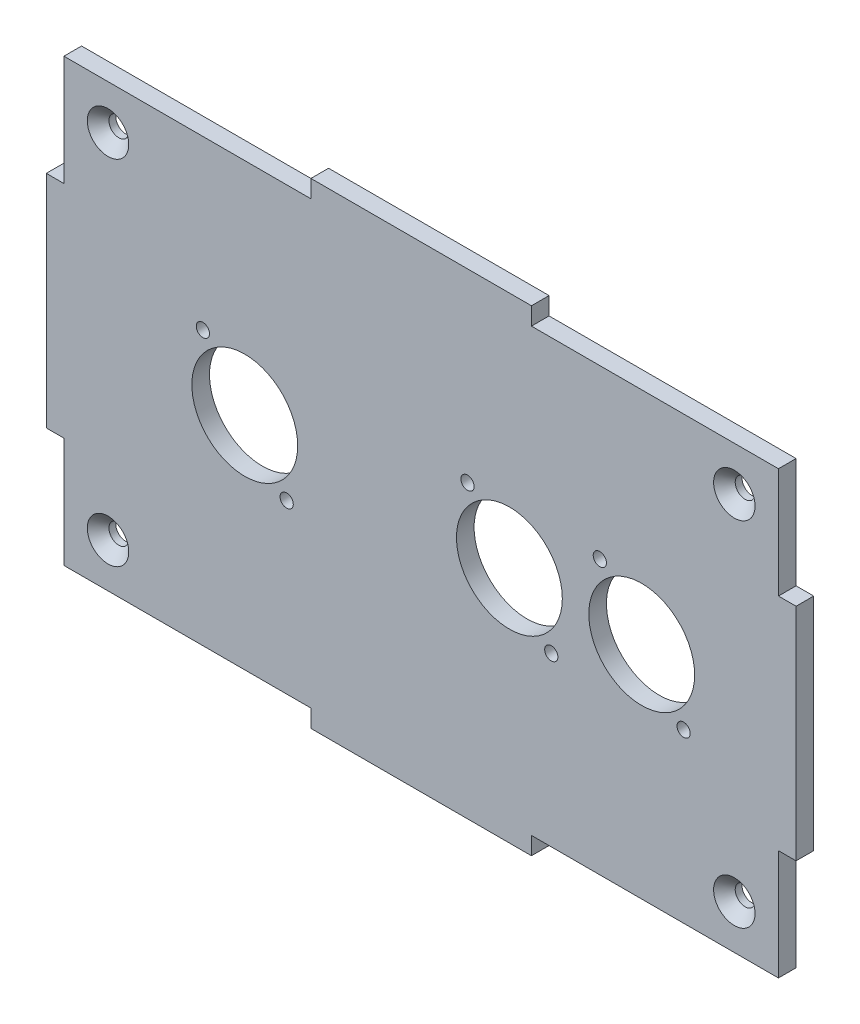
SolidWorks part; units mm, degrees
ref_plane "Front Plane" through (0, 0, 0) normal (0, 0, 1) x (1, 0, 0)
ref_plane "Top Plane" through (0, 0, 0) normal (0, 1, 0) x (1, 0, 0)
ref_plane "Right Plane" through (0, 0, 0) normal (1, 0, 0) x (0, 0, -1)
sketch "Sketch1" plane through (0, 0, 0) normal (0, 0, 1) x (1, 0, 0)
  line L0 (0, 54) -> (0, 0) construction
  line L1 (-81, -50) -> (81, -50)
  line L2 (-81, -50) -> (-81, 50)
  line L3 (-81, 50) -> (81, 50)
  line L4 (81, -50) -> (81, 50)
  line L5 (-81, -50) -> (81, 50) construction
  line L6 (-81, 50) -> (81, -50) construction
  line L7 (-81, 25) -> (-85, 25)
  line L8 (-81, 25) -> (-81, -25)
  line L9 (-81, -25) -> (-85, -25)
  line L10 (-85, 25) -> (-85, -25)
  line L11 (-25, 50) -> (25, 50)
  line L12 (-25, 50) -> (-25, 54)
  line L13 (-25, 54) -> (25, 54)
  line L14 (25, 50) -> (25, 54)
  line L15 (0, 0) -> (-85, 0) construction
  line L16 (25, -50) -> (25, -54)
  line L17 (-25, -50) -> (25, -50)
  line L18 (-25, -50) -> (-25, -54)
  line L19 (-25, -54) -> (25, -54)
  line L20 (81, -25) -> (85, -25)
  line L21 (85, 25) -> (85, -25)
  line L22 (81, 25) -> (85, 25)
  line L23 (81, 25) -> (81, -25)
  point P0 (0, 0)
  dimension "D1" = 162
  dimension "D2" = 100
  dimension "D3" = 4
  dimension "D4" = 4
  dimension "D5" = 50
  dimension "D6" = 50
extrude "Boss-Extrude2" add sketch "Sketch1" along normal blind 4 contours L1 L4 L3 L2 | L3 L14 L13 L12 | L22 L4 L20 L21 | L7 L10 L9 L2 | L19 L16 L17 L18
sketch "Sketch2" plane through (0, 0, 4) normal (0, 0, 1) x (1, 0, 0)
  line L0 (-40, 0) -> (0, 0)
  line L1 (0, 0) -> (20, 0)
  line L2 (20, 0) -> (50, 0)
  circle A0 centre (-40, 0) radius 12
  circle A1 centre (20, 0) radius 12
  circle A2 centre (50, 0) radius 12
  dimension "D1" = 24
  dimension "D2" = 40
  dimension "D3" = 20
  dimension "D4" = 30
extrude "Cut-Extrude1" cut sketch "Sketch2" against normal up to next
sketch "Sketch3" plane through (0, 0, 4) normal (0, 0, 1) x (1, 0, 0)
  line L0 (-81, 50) -> (-25, 50) construction
  line L1 (-71, 40) -> (71, 40)
  line L2 (-71, 40) -> (-71, -40)
  line L3 (-71, -40) -> (71, -40)
  line L4 (71, 40) -> (71, -40)
  line L5 (-81, 25) -> (-81, 50) construction
  line L6 (81, 25) -> (81, 50) construction
  line L7 (25, -50) -> (81, -50) construction
  dimension "D1" = 10
  dimension "D2" = 10
  dimension "D3" = 10
  dimension "D4" = 10
hole_wizard "CSK for M4 Countersunk Flat Head Screw1" positions "3DSketch1" profile "Sketch4" countersink size "M4" standard "ISO" end condition up to next
sketch3d "3DSketch1"
  point P0 (-71, 40, 4)
  point P3 (71, 40, 4)
  point P6 (71, -40, 4)
  point P9 (-71, -40, 4)
sketch "Sketch4" plane through (-71, 40, 4) normal (1, 0, 0) x (0, -1, 0)
  line L0 (0, 0) -> (0, 4)
  line L1 (0, 4) -> (2.25, 4)
  line L2 (2.25, 4) -> (2.25, 2.45)
  line L3 (2.25, 2.45) -> (4.7, 0)
  line L5 (4.7, 0) -> (0, 0)
  line L6 (-2.25, 2.45) -> (-4.7, 0) construction
  line L11 (0, -6.35) -> (0, 107.95) construction
  dimension "Thru Hole Dia." = 4.5
  dimension "Thru Hole Depth" = 4
  dimension "Near C'Sink Dia." = 9.4
  dimension "Near C'Sink Angle" = 90
sketch "Sketch5" plane through (0, 0, 4) normal (0, 0, 1) x (1, 0, 0)
  line L1 (-49.5, -12) -> (-30.5, -12)
  line L2 (-49.5, -12) -> (-49.5, 12)
  line L3 (-49.5, 12) -> (-30.5, 12)
  line L4 (-30.5, -12) -> (-30.5, 12)
  line L5 (-49.5, -12) -> (-30.5, 12) construction
  line L6 (-49.5, 12) -> (-30.5, -12) construction
  line L7 (10.5, -12) -> (29.5, -12)
  line L8 (10.5, -12) -> (10.5, 12)
  line L9 (10.5, 12) -> (29.5, 12)
  line L10 (29.5, -12) -> (29.5, 12)
  line L11 (10.5, -12) -> (29.5, 12) construction
  line L12 (10.5, 12) -> (29.5, -12) construction
  line L13 (40.5, -12) -> (59.5, -12)
  line L14 (40.5, -12) -> (40.5, 12)
  line L15 (40.5, 12) -> (59.5, 12)
  line L16 (59.5, -12) -> (59.5, 12)
  line L17 (40.5, -12) -> (59.5, 12) construction
  line L18 (40.5, 12) -> (59.5, -12) construction
  circle A0 centre (-40, 0) radius 12 construction
  circle A1 centre (-40, 0) radius 12
  circle A2 centre (20, 0) radius 12 construction
  circle A3 centre (20, 0) radius 12
  circle A4 centre (50, 0) radius 12 construction
  circle A5 centre (50, 0) radius 12
  dimension "D1" = 19
  dimension "D2" = 24
hole_wizard "Ø3.0mm Dowel Hole1" positions "3DSketch2" profile "Sketch6" hole size "Ø3.0" standard "ISO" end condition up to next
sketch3d "3DSketch2"
  point P0 (-49.5, 12, 4)
  point P3 (-30.5, -12, 4)
  point P6 (10.5, 12, 4)
  point P9 (29.5, -12, 4)
  point P12 (40.5, 12, 4)
  point P15 (59.5, -12, 4)
sketch "Sketch6" plane through (-49.5, 12, 4) normal (1, 0, 0) x (0, -1, 0)
  line L0 (0, 0) -> (0, 4)
  line L1 (0, 4) -> (1.5, 4)
  line L2 (1.5, 4) -> (1.5, 0)
  line L5 (1.5, 0) -> (0, 0)
  line L11 (0, -6.35) -> (0, 107.95) construction
  dimension "Thru Hole Dia." = 3
  dimension "Thru Hole Depth" = 4
